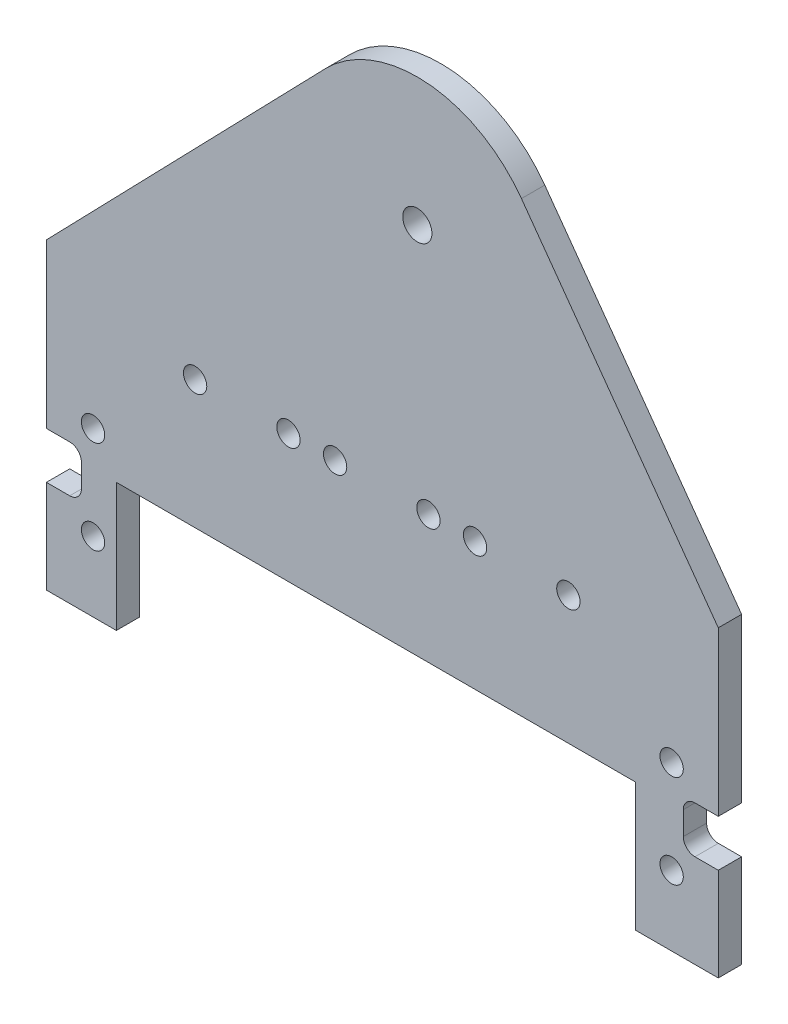
SolidWorks part; units mm, degrees
material "自訂玻璃纖維"
ref_plane "前基準面" through (0, 0, 0) normal (0, 0, 1) x (1, 0, 0)
ref_plane "上基準面" through (0, 0, 0) normal (0, 1, 0) x (1, 0, 0)
ref_plane "右基準面" through (0, 0, 0) normal (1, 0, 0) x (0, 0, -1)
sketch "草圖1" plane through (0, 0, 0) normal (0, 0, 1) x (1, 0, 0)
  line L0 (-28.8, -32) -> (-28.8, -34)
  line L1 (-31.8, -31) -> (-29.8, -31)
  line L2 (22.8, -32) -> (22.8, -34)
  line L3 (-31.8, -35) -> (-29.8, -35)
  line L4 (-31.8, -18) -> (-31.8, -31)
  line L5 (-25.8, -32) -> (18.7, -32)
  line L6 (-25.8, -43) -> (-26.8, -43)
  line L7 (-31.8, -17) -> (-7.8981, 7.6564)
  line L8 (-31.8, -42) -> (-31.8, -43)
  line L9 (-31.8, -43) -> (-30.8, -43)
  line L10 (25.8, -18) -> (25.8, -31)
  line L11 (-31.8, -36) -> (-31.8, -42)
  line L12 (-30.8, -43) -> (-26.8, -43)
  line L13 (18.7, -43) -> (18.7, -32)
  line L14 (18.7, -43) -> (24.8, -43)
  line L15 (25.8, -42) -> (25.8, -36)
  line L16 (25.8, -17) -> (8.9259, 6.4287)
  line L17 (25.8, -42) -> (25.8, -43)
  line L18 (25.8, -43) -> (24.8, -43)
  line L19 (-31.8, -18) -> (-31.8, -17)
  line L20 (25.8, -18) -> (25.8, -17)
  line L23 (-31.8, -35) -> (-31.8, -36)
  line L24 (25.8, -31) -> (23.8, -31)
  line L26 (25.8, -35) -> (23.8, -35)
  line L27 (25.8, -35) -> (25.8, -36)
  line L31 (-25.8, -32) -> (-25.8, -43)
  circle A0 centre (0, 0) radius 1.25
  arc A1 (-29.8, -31) -> (-28.8, -32) centre (-29.8, -32) cw
  arc A2 (-28.8, -34) -> (-29.8, -35) centre (-29.8, -34) cw
  arc A3 (23.8, -31) -> (22.8, -32) centre (23.8, -32) ccw
  arc A4 (22.8, -34) -> (23.8, -35) centre (23.8, -34) ccw
  arc A5 (8.9259, 6.4287) -> (-7.8981, 7.6564) centre (0, 0) ccw
  circle A6 centre (-19.05, -21) radius 1
  circle A7 centre (-11.05, -21) radius 1
  circle A8 centre (4.95, -21) radius 1
  circle A9 centre (12.95, -21) radius 1
  circle A10 centre (-27.8, -29) radius 1
  circle A11 centre (-27.8, -37) radius 1
  circle A12 centre (21.8, -37) radius 1
  circle A13 centre (21.8, -29) radius 1
  circle A24 centre (-7.05, -21) radius 1
  circle A25 centre (0.95, -21) radius 1
  point P17 (-31.8, -43)
  point P18 (-31.8, -17)
  point P21 (0, 0)
  point P43 (17.7, -37)
  point P46 (25.8, -37)
  point P49 (25.8, -17)
  point P52 (-31.8, -17)
  point P55 (-31.8, -37)
  point P58 (-25.8, -37)
  point P65 (11, -17)
  dimension "D3" = 2.5
  dimension "D5" = 22
  dimension "D6" = 4
  dimension "D13" = 8
  dimension "D14" = 2
  dimension "D15" = 4
  dimension "D16" = 6
  dimension "D17" = 6
  dimension "D19" = 2
  dimension "D20" = 8
  dimension "D21" = 8
  dimension "D22" = 2
  dimension "D23" = 2
  dimension "D24" = 32.75
  dimension "D4" = 4
  dimension "D25" = 4
  dimension "D28" = 2
  dimension "D30" = 2
  dimension "D31" = 4
  dimension "D32" = 4
  dimension "D33" = 0
  dimension "D34" = 0
  dimension "D7" = 57.6
  dimension "D8" = 25.8
  dimension "D9" = 20
  dimension "D10" = 6
  dimension "D11" = 8.1
  dimension "D12" = 2
  dimension "D18" = 18
  dimension "D26" = 7
  dimension "D27" = 8
  dimension "D29" = 8
extrude "填料-伸長1" add sketch "草圖1" along normal blind 2
